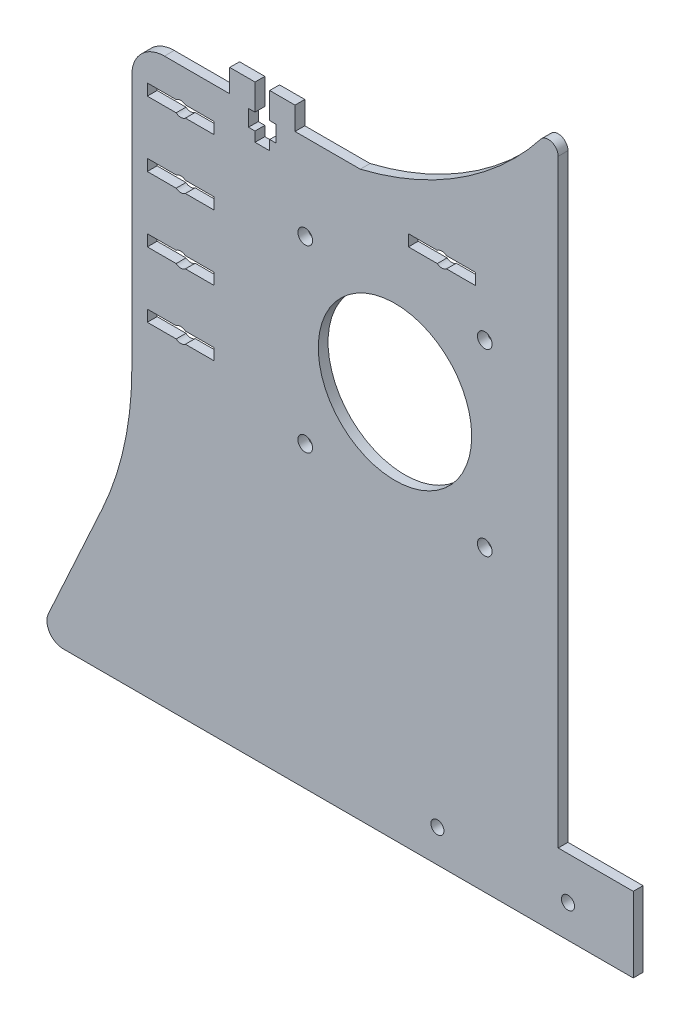
SolidWorks part; units mm, degrees
ref_plane "前视基准面" through (0, 0, 0) normal (0, 0, 1) x (1, 0, 0)
ref_plane "上视基准面" through (0, 0, 0) normal (0, 1, 0) x (1, 0, 0)
ref_plane "右视基准面" through (0, 0, 0) normal (1, 0, 0) x (0, 0, -1)
other "Configuration Table"
sketch "草图1" plane through (0, 0, 0) normal (0, 0, 1) x (1, 0, 0)
  line L0 (-980.9001, -119) -> (49019.0999, -119) construction
  line L1 (-80.6279, -56.0594) -> (-109.4203, -119)
  line L2 (50, -1119) -> (50, -119) construction
  line L3 (-28.9769, 40.7472) -> (50, 96.9107) construction
  line L4 (50, 96.9107) -> (50, -96)
  line L5 (50, -119) -> (-109.4203, -119)
  line L6 (-10.6279, 53.7959) -> (-28.9769, 40.7472)
  line L7 (50, -96) -> (50, 48881) construction
  line L8 (50, -119) -> (73, -119)
  line L10 (50, -96) -> (73, -96)
  line L11 (73, -119) -> (73, -96)
  line L12 (-10.6279, 53.7959) -> (-80.6279, 53.7959)
  line L13 (-80.6279, 53.7959) -> (-80.6279, -56.0594)
  line L14 (-64.305, 40.7959) -> (-55.6279, 40.7959)
  line L15 (-75.6279, 43.7959) -> (-66.9508, 43.7959)
  line L16 (-75.6279, 43.7959) -> (-75.6279, 40.7959)
  line L17 (-75.6279, 40.7959) -> (-66.9508, 40.7959)
  line L18 (-55.6279, 43.7959) -> (-55.6279, 40.7959)
  line L19 (-75.6279, 43.7959) -> (-55.6279, 40.7959) construction
  line L20 (-75.6279, 40.7959) -> (-55.6279, 43.7959) construction
  line L21 (-64.305, 43.7959) -> (-55.6279, 43.7959)
  line L22 (-75.6279, 20.7959) -> (-66.9508, 20.7959)
  line L23 (-64.305, 20.7959) -> (-55.6279, 20.7959)
  line L24 (-55.6279, 23.7959) -> (-55.6279, 20.7959)
  line L25 (-64.305, 23.7959) -> (-55.6279, 23.7959)
  line L26 (-75.6279, 23.7959) -> (-66.9508, 23.7959)
  line L27 (-75.6279, 23.7959) -> (-75.6279, 20.7959)
  line L28 (-75.6279, 0.7959) -> (-66.9508, 0.7959)
  line L29 (-64.305, 0.7959) -> (-55.6279, 0.7959)
  line L30 (-55.6279, 3.7959) -> (-55.6279, 0.7959)
  line L31 (-64.305, 3.7959) -> (-55.6279, 3.7959)
  line L32 (-75.6279, 3.7959) -> (-66.9508, 3.7959)
  line L33 (-75.6279, 3.7959) -> (-75.6279, 0.7959)
  line L34 (-75.6279, -19.2041) -> (-66.9508, -19.2041)
  line L35 (-64.305, -19.2041) -> (-55.6279, -19.2041)
  line L36 (-55.6279, -16.2041) -> (-55.6279, -19.2041)
  line L37 (-64.305, -16.2041) -> (-55.6279, -16.2041)
  line L38 (-75.6279, -16.2041) -> (-66.9508, -16.2041)
  line L39 (-75.6279, -16.2041) -> (-75.6279, -19.2041)
  circle A0 centre (0, 0) radius 23.5
  circle A1 centre (0, 0) radius 50
  arc A4 (-10.6279, 53.7959) -> (50, 96.9107) centre (-34.1092, 151) ccw
  circle A5 centre (53, -109) radius 2 construction
  circle A7 centre (53, -109) radius 2
  arc A11 (-64.305, 43.7959) -> (-66.9508, 43.7959) centre (-65.6279, 42.2959) ccw
  arc A12 (-66.9508, 20.7959) -> (-64.305, 20.7959) centre (-65.6279, 22.2959) ccw
  arc A13 (-66.9508, 40.7959) -> (-64.305, 40.7959) centre (-65.6279, 42.2959) ccw
  arc A14 (-64.305, 23.7959) -> (-66.9508, 23.7959) centre (-65.6279, 22.2959) ccw
  arc A15 (-66.9508, 0.7959) -> (-64.305, 0.7959) centre (-65.6279, 2.2959) ccw
  arc A16 (-64.305, 3.7959) -> (-66.9508, 3.7959) centre (-65.6279, 2.2959) ccw
  arc A17 (-66.9508, -19.2041) -> (-64.305, -19.2041) centre (-65.6279, -17.7041) ccw
  arc A18 (-64.305, -16.2041) -> (-66.9508, -16.2041) centre (-65.6279, -17.7041) ccw
  circle A19 centre (13, -109) radius 2
  point P6 (-65.6279, 42.2959)
  dimension "D1" = 47
  dimension "D2" = 119
  dimension "D3" = 100
  dimension "D4" = 50
  dimension "D13" = 4
  dimension "D16" = 4
  dimension "D17" = 40
  dimension "D18" = 10
  dimension "D19" = 100
  dimension "D5" = 150
  dimension "D6" = 23
  dimension "D7" = 23
  dimension "D8" = 70
  dimension "D9" = 3
  dimension "D10" = 20
  dimension "D11" = 5
  dimension "D12" = 10
  dimension "D15" = 20
  dimension "D20" = 130.6279
  dimension "D21" = 65.418
  dimension "D14" = 4
extrude "凸台-拉伸1" add sketch "草图1" along normal blind 3 contours A1 L1 L5 L4 | A1 A0 | A1 L4 L3
sketch "草图2" plane through (0, 0, 3) normal (0, 0, 1) x (1, 0, 0)
  line L1 (-27.5, 27.5) -> (27.5, 27.5) construction
  line L2 (-27.5, 27.5) -> (-27.5, -27.5) construction
  line L3 (-27.5, -27.5) -> (27.5, -27.5) construction
  line L4 (27.5, 27.5) -> (27.5, -27.5) construction
  line L5 (-27.5, 27.5) -> (27.5, -27.5) construction
  line L6 (-27.5, -27.5) -> (27.5, 27.5) construction
  circle A0 centre (-27.5, 27.5) radius 2.25
  circle A1 centre (27.5, 27.5) radius 2.25
  circle A2 centre (27.5, -27.5) radius 2.25
  circle A3 centre (-27.5, -27.5) radius 2.25
  point P0 (0, 0)
  dimension "D2" = 4.5
  dimension "D3" = 4.5
  dimension "D4" = 4.5
  dimension "D5" = 4.5
  dimension "D1" = 55
extrude "切除-拉伸1" cut sketch "草图2" against normal through all
fillet "圆角1" radius 10 1 edges at (-80.6279, 53.7959, 1.5)
fillet "圆角2" radius 100 1 edges at (-80.6279, -56.0594, 1.5)
fillet "圆角3" radius 5 1 edges at (-109.4203, -119, 1.5)
sketch "草图3" plane through (0, 0, 3) normal (0, 0, 1) x (1, 0, 0)
  line L0 (-10.6279, 53.7959) -> (-70.6279, 53.7959) construction
  line L1 (-50.6279, 53.7959) -> (-30.6279, 53.7959)
  line L2 (-50.6279, 53.7959) -> (-50.6279, 60.7959)
  line L3 (-50.6279, 60.7959) -> (-30.6279, 60.7959)
  line L4 (-30.6279, 53.7959) -> (-30.6279, 60.7959)
  line L5 (-55.6279, 43.7959) -> (-55.6279, 40.7959) construction
  dimension "D1" = 7
  dimension "D2" = 20
  dimension "D3" = 5
extrude "凸台-拉伸2" add sketch "草图3" against normal blind 3
sketch "草图4" plane through (0, 0, 3) normal (0, 0, 1) x (1, 0, 0)
  line L0 (-64.305, 43.7959) -> (-55.6279, 43.7959) construction
  line L1 (4.3721, 43.7959) -> (24.3721, 43.7959)
  line L2 (4.3721, 43.7959) -> (4.3721, 40.7959)
  line L3 (4.3721, 40.7959) -> (24.3721, 40.7959)
  line L4 (24.3721, 43.7959) -> (24.3721, 40.7959)
  line L5 (4.3721, 43.7959) -> (24.3721, 40.7959) construction
  line L6 (4.3721, 40.7959) -> (24.3721, 43.7959) construction
  line L7 (-55.6279, 43.7959) -> (-55.6279, 40.7959) construction
  circle A0 centre (14.3721, 42.2959) radius 2
  point P0 (14.3721, 42.2959)
  dimension "D3" = 4
  dimension "D1" = 3
  dimension "D2" = 20
  dimension "D4" = 60
extrude "切除-拉伸2" cut sketch "草图4" against normal blind 10 contours L1 A0 L3 | L1 A0 | L3 A0 | A0 L3 L4 L1 | A0 L1 L2 L3
fillet "圆角4" radius 3 1 edges at (50, 96.9107, 1.5)
sketch "草图5" plane through (0, 0, 3) normal (0, 0, 1) x (1, 0, 0)
  line L0 (-42.8779, 60.7959) -> (-42.8779, 52.7959)
  line L1 (-30.6279, 60.7959) -> (-50.6279, 60.7959) construction
  line L2 (-42.8779, 52.7959) -> (-44.8779, 52.7959)
  line L3 (-44.8779, 52.7959) -> (-44.8779, 47.7959)
  line L4 (-44.8779, 47.7959) -> (-42.8779, 47.7959)
  line L5 (-42.8779, 47.7959) -> (-42.8779, 44.7959)
  line L6 (-42.8779, 44.7959) -> (-38.3779, 44.7959)
  line L7 (-38.3779, 44.7959) -> (-38.3779, 47.7959)
  line L8 (-38.3779, 47.7959) -> (-36.3779, 47.7959)
  line L9 (-36.3779, 47.7959) -> (-36.3779, 52.7959)
  line L10 (-36.3779, 52.7959) -> (-38.3779, 52.7959)
  line L11 (-38.3779, 52.7959) -> (-38.3779, 60.7959)
  line L12 (-50.6279, 60.7959) -> (-50.6279, 53.7959) construction
  line L13 (-38.3779, 60.7959) -> (-42.8779, 60.7959)
  point P14 (-40.6279, 44.7959)
  dimension "D1" = 8
  dimension "D2" = 2
  dimension "D3" = 5
  dimension "D4" = 2
  dimension "D5" = 3
  dimension "D6" = 4.5
  dimension "D7" = 3
  dimension "D8" = 2
  dimension "D9" = 5
  dimension "D10" = 2
  dimension "D11" = 10
extrude "切除-拉伸3" cut sketch "草图5" against normal blind 3
sketch "草图7" plane through (0, 0, 3) normal (0, 0, 1) x (1, 0, 0)
  line L0 (4.3721, 43.7959) -> (4.3721, 40.7959) construction
  line L1 (4.3721, 43.7959) -> (13.0492, 43.7959) construction
  line L2 (4.3721, 40.7959) -> (13.0492, 40.7959) construction
  line L3 (24.3721, 43.7959) -> (24.3721, 40.7959) construction
  line L4 (15.695, 43.7959) -> (24.3721, 43.7959) construction
  line L5 (15.695, 40.7959) -> (24.3721, 40.7959) construction
  line L6 (-75.6279, -19.2041) -> (-66.9508, -19.2041) construction
  line L7 (-75.6279, -16.2041) -> (-75.6279, -19.2041) construction
  line L8 (-75.6279, -16.2041) -> (-66.9508, -16.2041) construction
  line L9 (-64.305, -16.2041) -> (-55.6279, -16.2041) construction
  line L10 (-55.6279, -16.2041) -> (-55.6279, -19.2041) construction
  line L11 (-64.305, -19.2041) -> (-55.6279, -19.2041) construction
  line L12 (-75.6279, 3.7959) -> (-75.6279, 0.7959) construction
  line L13 (-75.6279, 3.7959) -> (-66.9508, 3.7959) construction
  line L14 (-75.6279, 0.7959) -> (-66.9508, 0.7959) construction
  line L15 (-64.305, 0.7959) -> (-55.6279, 0.7959) construction
  line L16 (-55.6279, 3.7959) -> (-55.6279, 0.7959) construction
  line L17 (-64.305, 3.7959) -> (-55.6279, 3.7959) construction
  line L18 (-75.6279, 23.7959) -> (-75.6279, 20.7959) construction
  line L19 (-75.6279, 20.7959) -> (-66.9508, 20.7959) construction
  line L20 (-64.305, 20.7959) -> (-55.6279, 20.7959) construction
  line L21 (-55.6279, 23.7959) -> (-55.6279, 20.7959) construction
  line L22 (-64.305, 23.7959) -> (-55.6279, 23.7959) construction
  line L23 (-75.6279, 23.7959) -> (-66.9508, 23.7959) construction
  line L24 (-64.305, 43.7959) -> (-55.6279, 43.7959) construction
  line L25 (-55.6279, 43.7959) -> (-55.6279, 40.7959) construction
  line L26 (-64.305, 40.7959) -> (-55.6279, 40.7959) construction
  line L27 (-75.6279, 40.7959) -> (-66.9508, 40.7959) construction
  line L28 (-75.6279, 43.7959) -> (-75.6279, 40.7959) construction
  line L29 (-75.6279, 43.7959) -> (-66.9508, 43.7959) construction
  line L30 (4.3721, 43.7959) -> (4.3721, 40.7959)
  line L31 (4.3721, 43.7959) -> (13.0492, 43.7959)
  line L32 (4.3721, 40.7959) -> (13.0492, 40.7959)
  line L33 (24.3721, 43.7959) -> (24.3721, 40.7959)
  line L34 (15.695, 43.7959) -> (24.3721, 43.7959)
  line L35 (15.695, 40.7959) -> (24.3721, 40.7959)
  line L36 (-75.6279, -19.2041) -> (-66.9508, -19.2041)
  line L37 (-75.6279, -16.2041) -> (-75.6279, -19.2041)
  line L38 (-75.6279, -16.2041) -> (-66.9508, -16.2041)
  line L39 (-64.305, -16.2041) -> (-55.6279, -16.2041)
  line L40 (-55.6279, -16.2041) -> (-55.6279, -19.2041)
  line L41 (-64.305, -19.2041) -> (-55.6279, -19.2041)
  line L42 (-75.6279, 3.7959) -> (-75.6279, 0.7959)
  line L43 (-75.6279, 3.7959) -> (-66.9508, 3.7959)
  line L44 (-75.6279, 0.7959) -> (-66.9508, 0.7959)
  line L45 (-64.305, 0.7959) -> (-55.6279, 0.7959)
  line L46 (-55.6279, 3.7959) -> (-55.6279, 0.7959)
  line L47 (-64.305, 3.7959) -> (-55.6279, 3.7959)
  line L48 (-75.6279, 23.7959) -> (-75.6279, 20.7959)
  line L49 (-75.6279, 20.7959) -> (-66.9508, 20.7959)
  line L50 (-64.305, 20.7959) -> (-55.6279, 20.7959)
  line L51 (-55.6279, 23.7959) -> (-55.6279, 20.7959)
  line L52 (-64.305, 23.7959) -> (-55.6279, 23.7959)
  line L53 (-75.6279, 23.7959) -> (-66.9508, 23.7959)
  line L54 (-64.305, 43.7959) -> (-55.6279, 43.7959)
  line L55 (-55.6279, 43.7959) -> (-55.6279, 40.7959)
  line L56 (-64.305, 40.7959) -> (-55.6279, 40.7959)
  line L57 (-75.6279, 40.7959) -> (-66.9508, 40.7959)
  line L58 (-75.6279, 43.7959) -> (-75.6279, 40.7959)
  line L59 (-75.6279, 43.7959) -> (-66.9508, 43.7959)
  line L60 (-75.8779, 44.0459) -> (-67.0421, 44.0459)
  line L61 (-75.8779, 44.0459) -> (-75.8779, 40.5459)
  line L62 (-75.8779, 40.5459) -> (-67.0421, 40.5459)
  line L63 (-64.2137, 40.5459) -> (-55.3779, 40.5459)
  line L64 (-55.3779, 44.0459) -> (-55.3779, 40.5459)
  line L65 (-64.2137, 44.0459) -> (-55.3779, 44.0459)
  line L66 (-75.8779, 24.0459) -> (-75.8779, 20.5459)
  line L67 (-75.8779, 20.5459) -> (-67.0421, 20.5459)
  line L68 (-64.2137, 20.5459) -> (-55.3779, 20.5459)
  line L69 (-55.3779, 24.0459) -> (-55.3779, 20.5459)
  line L70 (-64.2137, 24.0459) -> (-55.3779, 24.0459)
  line L71 (-75.8779, 24.0459) -> (-67.0421, 24.0459)
  line L72 (-75.8779, 4.0459) -> (-75.8779, 0.5459)
  line L73 (-75.8779, 0.5459) -> (-67.0421, 0.5459)
  line L74 (-64.2137, 0.5459) -> (-55.3779, 0.5459)
  line L75 (-55.3779, 4.0459) -> (-55.3779, 0.5459)
  line L76 (-64.2137, 4.0459) -> (-55.3779, 4.0459)
  line L77 (-75.8779, 4.0459) -> (-67.0421, 4.0459)
  line L78 (-75.8779, -19.4541) -> (-67.0421, -19.4541)
  line L79 (-64.2137, -19.4541) -> (-55.3779, -19.4541)
  line L80 (-55.3779, -15.9541) -> (-55.3779, -19.4541)
  line L81 (-64.2137, -15.9541) -> (-55.3779, -15.9541)
  line L82 (-75.8779, -15.9541) -> (-67.0421, -15.9541)
  line L83 (-75.8779, -15.9541) -> (-75.8779, -19.4541)
  line L84 (4.1221, 44.0459) -> (4.1221, 40.5459)
  line L85 (4.1221, 40.5459) -> (12.9579, 40.5459)
  line L86 (15.7863, 40.5459) -> (24.6221, 40.5459)
  line L87 (24.6221, 44.0459) -> (24.6221, 40.5459)
  line L88 (15.7863, 44.0459) -> (24.6221, 44.0459)
  line L89 (4.1221, 44.0459) -> (12.9579, 44.0459)
  arc A0 (15.695, 43.7959) -> (13.0492, 43.7959) centre (14.3721, 42.2959) ccw construction
  arc A1 (13.0492, 40.7959) -> (15.695, 40.7959) centre (14.3721, 42.2959) ccw construction
  arc A2 (-64.305, -16.2041) -> (-66.9508, -16.2041) centre (-65.6279, -17.7041) ccw construction
  arc A3 (-66.9508, -19.2041) -> (-64.305, -19.2041) centre (-65.6279, -17.7041) ccw construction
  arc A4 (-64.305, 3.7959) -> (-66.9508, 3.7959) centre (-65.6279, 2.2959) ccw construction
  arc A5 (-66.9508, 0.7959) -> (-64.305, 0.7959) centre (-65.6279, 2.2959) ccw construction
  arc A6 (-66.9508, 20.7959) -> (-64.305, 20.7959) centre (-65.6279, 22.2959) ccw construction
  arc A7 (-64.305, 23.7959) -> (-66.9508, 23.7959) centre (-65.6279, 22.2959) ccw construction
  arc A8 (-64.305, 43.7959) -> (-66.9508, 43.7959) centre (-65.6279, 42.2959) ccw construction
  arc A9 (-66.9508, 40.7959) -> (-64.305, 40.7959) centre (-65.6279, 42.2959) ccw construction
  arc A10 (15.695, 43.7959) -> (13.0492, 43.7959) centre (14.3721, 42.2959) ccw
  arc A11 (13.0492, 40.7959) -> (15.695, 40.7959) centre (14.3721, 42.2959) ccw
  arc A12 (-64.305, -16.2041) -> (-66.9508, -16.2041) centre (-65.6279, -17.7041) ccw
  arc A13 (-66.9508, -19.2041) -> (-64.305, -19.2041) centre (-65.6279, -17.7041) ccw
  arc A14 (-64.305, 3.7959) -> (-66.9508, 3.7959) centre (-65.6279, 2.2959) ccw
  arc A15 (-66.9508, 0.7959) -> (-64.305, 0.7959) centre (-65.6279, 2.2959) ccw
  arc A16 (-66.9508, 20.7959) -> (-64.305, 20.7959) centre (-65.6279, 22.2959) ccw
  arc A17 (-64.305, 23.7959) -> (-66.9508, 23.7959) centre (-65.6279, 22.2959) ccw
  arc A18 (-64.305, 43.7959) -> (-66.9508, 43.7959) centre (-65.6279, 42.2959) ccw
  arc A19 (-66.9508, 40.7959) -> (-64.305, 40.7959) centre (-65.6279, 42.2959) ccw
  arc A20 (-64.2137, 44.0459) -> (-67.0421, 44.0459) centre (-65.6279, 42.2959) ccw
  arc A21 (-67.0421, 40.5459) -> (-64.2137, 40.5459) centre (-65.6279, 42.2959) ccw
  arc A22 (-67.0421, 20.5459) -> (-64.2137, 20.5459) centre (-65.6279, 22.2959) ccw
  arc A23 (-64.2137, 24.0459) -> (-67.0421, 24.0459) centre (-65.6279, 22.2959) ccw
  arc A24 (-67.0421, 0.5459) -> (-64.2137, 0.5459) centre (-65.6279, 2.2959) ccw
  arc A25 (-64.2137, 4.0459) -> (-67.0421, 4.0459) centre (-65.6279, 2.2959) ccw
  arc A26 (-67.0421, -19.4541) -> (-64.2137, -19.4541) centre (-65.6279, -17.7041) ccw
  arc A27 (-64.2137, -15.9541) -> (-67.0421, -15.9541) centre (-65.6279, -17.7041) ccw
  arc A28 (12.9579, 40.5459) -> (15.7863, 40.5459) centre (14.3721, 42.2959) ccw
  arc A29 (15.7863, 44.0459) -> (12.9579, 44.0459) centre (14.3721, 42.2959) ccw
  dimension "D1" = 0.25
  dimension "D2" = 0.25
  dimension "D3" = 0.25
  dimension "D4" = 0.25
  dimension "D5" = 0.25
extrude "切除-拉伸4" cut sketch "草图7" against normal blind 10
